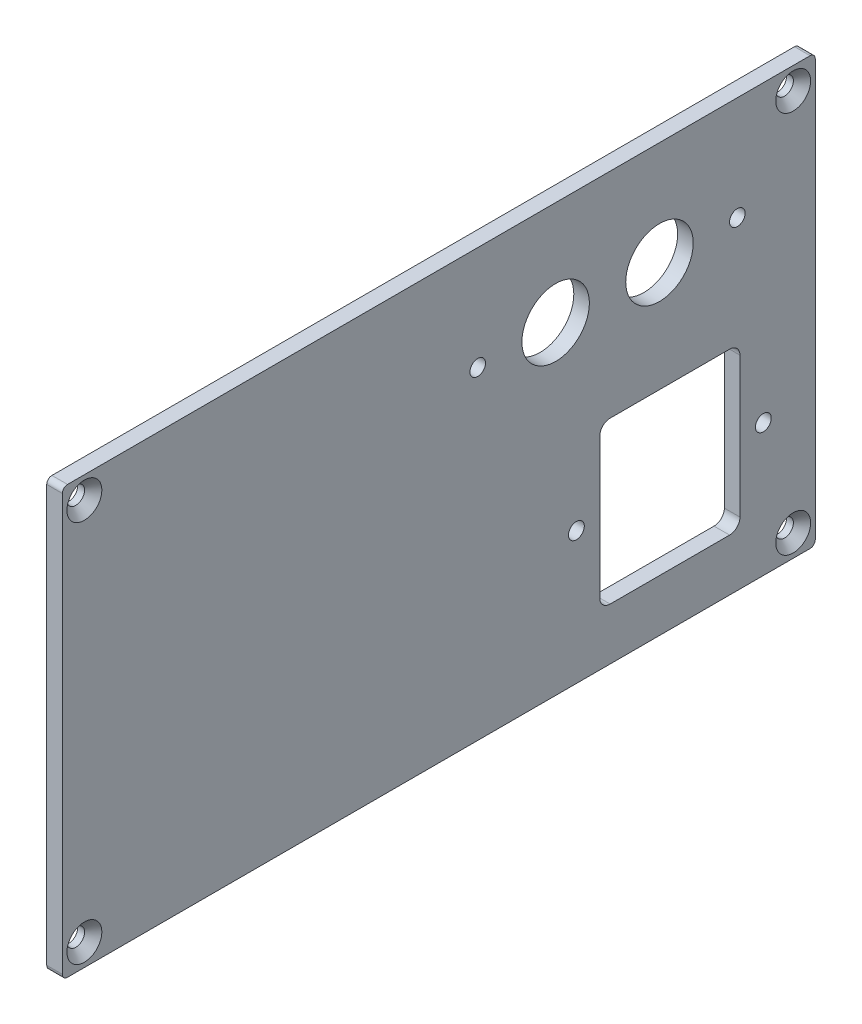
SolidWorks part; units mm, degrees
ref_plane "Front Plane" through (0, 0, 0) normal (0, 0, 1) x (1, 0, 0)
ref_plane "Top Plane" through (0, 0, 0) normal (0, 1, 0) x (1, 0, 0)
ref_plane "Right Plane" through (0, 0, 0) normal (1, 0, 0) x (0, 0, -1)
sketch "Sketch1" plane through (0, 0, 0) normal (1, 0, 0) x (0, 0, -1)
  line L0 (32.5, 39.5201) -> (32.5, 14.6747) construction
  line L1 (-71.5, 41.1) -> (71.5, 41.1)
  line L2 (-72.5, 40.1) -> (-72.5, -40.1)
  line L3 (-71.5, -41.1) -> (71.5, -41.1)
  line L4 (72.5, 40.1) -> (72.5, -40.1)
  line L5 (-72.5, 41.1) -> (72.5, -41.1) construction
  line L6 (-72.5, -41.1) -> (72.5, 41.1) construction
  line L8 (10.0417, -15.6) -> (65.295, -15.6) construction
  line L9 (33, -0.1) -> (56, -0.1)
  line L10 (31, -2.1) -> (31, -29.1)
  line L11 (33, -31.1) -> (56, -31.1)
  line L12 (58, -2.1) -> (58, -29.1)
  line L13 (44.5, 2.9321) -> (44.5, -44.8344) construction
  arc A0 (-72.5, -40.1) -> (-71.5, -41.1) centre (-71.5, -40.1) ccw
  arc A1 (-71.5, 41.1) -> (-72.5, 40.1) centre (-71.5, 40.1) ccw
  arc A2 (71.5, 41.1) -> (72.5, 40.1) centre (71.5, 40.1) cw
  arc A3 (71.5, -41.1) -> (72.5, -40.1) centre (71.5, -40.1) ccw
  arc A8 (56, -31.1) -> (58, -29.1) centre (56, -29.1) ccw
  arc A9 (31, -29.1) -> (33, -31.1) centre (33, -29.1) ccw
  arc A10 (33, -0.1) -> (31, -2.1) centre (33, -2.1) ccw
  arc A11 (56, -0.1) -> (58, -2.1) centre (56, -2.1) cw
  circle A12 centre (26.5, -15.6) radius 1.525
  circle A14 centre (62.5, -15.6) radius 1.525
  circle A15 centre (22.5, 21.1) radius 6.5
  circle A19 centre (7.5, 21.1) radius 1.5
  circle A20 centre (57.5, 21.1) radius 1.5
  circle A21 centre (42.5, 21.1) radius 6.5
  point P0 (0, 0)
  point P44 (44.5, -0.1)
  point P53 (58, -15.6)
  dimension "D3" = 1
  dimension "D4" = 13
  dimension "D11" = 2
  dimension "D9" = 3.05
  dimension "D14" = 10
  dimension "D6" = 3
  dimension "D1" = 145
  dimension "D2" = 82.2
  dimension "D5" = 20
  dimension "D7" = 27
  dimension "D8" = 31
  dimension "D10" = 36
  dimension "D12" = 10
  dimension "D13" = 10
  dimension "D15" = 25
  dimension "D16" = 40
extrude "Boss-Extrude1" add sketch "Sketch1" along normal blind 3
hole_wizard "CSK for M3 SFHCS1" positions "Sketch2" profile "Sketch3" countersink size "M3" standard "ANSI Metric" end condition through all
sketch "Sketch2" plane through (3, 0, 0) normal (1, 0, 0) x (0, 0, -1)
  line L0 (-72.5, 0) -> (72.5, 0) construction
  line L1 (-72.5, 40.1) -> (-72.5, -40.1) construction
  line L2 (72.5, -40.1) -> (72.5, 40.1) construction
  line L5 (71.5, 41.1) -> (-71.5, 41.1) construction
  line L6 (-71.5, -41.1) -> (71.5, -41.1) construction
  line L8 (0, -41.1) -> (0, 41.1) construction
  point P0 (-68.25, 36.85)
  point P31 (68.25, 36.85)
  point P33 (68.25, -36.85)
  point P34 (-68.25, -36.85)
  dimension "D1" = 73.7
  dimension "D2" = 136.5
sketch "Sketch3" plane through (3, 36.85, 68.25) normal (0, 1, 0) x (0, 0, -1)
  line L0 (0, 0) -> (0, 3)
  line L1 (0, 3) -> (1.7, 3)
  line L2 (1.7, 3) -> (1.7, 1.66)
  line L3 (1.7, 1.66) -> (3.36, 0)
  line L5 (3.36, 0) -> (0, 0)
  line L6 (-1.7, 1.66) -> (-3.36, 0) construction
  line L11 (0, -6.35) -> (0, 107.95) construction
  dimension "Thru Hole Dia." = 3.4
  dimension "Thru Hole Depth" = 3
  dimension "Near C'Sink Dia." = 6.72
  dimension "Near C'Sink Angle" = 90
